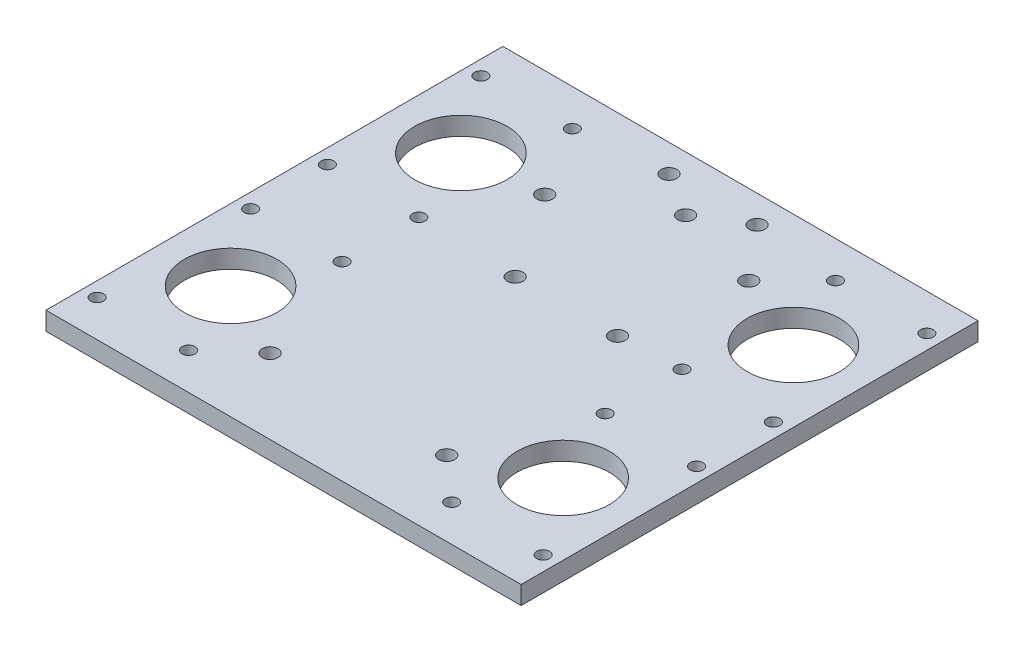
SolidWorks part; units mm, degrees
ref_plane "Front Plane" through (0, 0, 0) normal (0, 0, 1) x (1, 0, 0)
ref_plane "Top Plane" through (0, 0, 0) normal (0, 1, 0) x (1, 0, 0)
ref_plane "Right Plane" through (0, 0, 0) normal (1, 0, 0) x (0, 0, -1)
sketch "Sketch1" plane through (0, 0, 0) normal (0, 1, 0) x (1, 0, 0)
  line L1 (-65, 62.5) -> (65, 62.5)
  line L2 (-65, 62.5) -> (-65, -62.5)
  line L3 (-65, -62.5) -> (65, -62.5)
  line L4 (65, 62.5) -> (65, -62.5)
  line L5 (-65, 62.5) -> (65, -62.5) construction
  line L6 (-65, -62.5) -> (65, 62.5) construction
  point P0 (0, 0)
  dimension "D1" = 130
  dimension "D2" = 125
extrude "Boss-Extrude1" add sketch "Sketch1" along normal blind 5
sketch "Sketch2" plane through (0, 5, 0) normal (0, 1, 0) x (1, 0, 0)
  line L1 (-65, -62.5) -> (65, -62.5) construction
  line L2 (-65, 62.5) -> (-65, -62.5) construction
  circle A0 centre (-61, -52.5) radius 1.75
  circle A1 centre (-36, -52.5) radius 1.75
  circle A2 centre (-36, -10.5) radius 1.75
  circle A3 centre (-61, -10.5) radius 1.75
  circle A4 centre (-45.5, -31.5) radius 12.65
  dimension "D2" = 25.3
  dimension "D7" = 3.5
  dimension "D8" = 3.5
  dimension "D9" = 3.5
  dimension "D10" = 3.5
  dimension "D1" = 19.5
  dimension "D3" = 31
  dimension "D4" = 4
  dimension "D5" = 10
  dimension "D6" = 10
  dimension "D11" = 4
  dimension "D12" = 42
  dimension "D13" = 42
  dimension "D14" = 25
  dimension "D15" = 25
extrude "Cut-Extrude1" cut sketch "Sketch2" against normal blind 10
ref_plane "Plane1" through (0, 0, 0) normal (-1, 0, 0) x (0, 0, 1)
ref_plane "Plane2" through (0, 0, 0) normal (0, 0, 1) x (1, 0, 0)
mirror "Mirror3" about plane through (0, 0, 0) normal (-1, 0, 0) of "Cut-Extrude1"
mirror "Mirror4" about plane through (0, 0, 0) normal (0, 0, 1) of "Mirror3", "Cut-Extrude1"
sketch "Sketch3" plane through (0, 5, 0) normal (0, 1, 0) x (1, 0, 0)
  line L0 (-65, -62.5) -> (65, -62.5) construction
  line L1 (-65, 62.5) -> (-65, -62.5) construction
  line L2 (65, -62.5) -> (65, 62.5) construction
  line L3 (65, 62.5) -> (-65, 62.5) construction
  circle A0 centre (-24.17, -42.03) radius 2.15
  circle A1 centre (24.17, -42.03) radius 2.15
  circle A2 centre (-8.73, 9.6) radius 2.15
  circle A3 centre (19.29, 9.6) radius 2.15
  circle A4 centre (-24.17, 33.11) radius 2.15
  circle A5 centre (24.17, 40.6) radius 2.15
  dimension "D1" = 4.3
  dimension "D6" = 4.3
  dimension "D7" = 4.3
  dimension "D10" = 4.3
  dimension "D11" = 4.3
  dimension "D12" = 4.3
  dimension "D2" = 20.47
  dimension "D3" = 40.83
  dimension "D4" = 20.47
  dimension "D5" = 40.83
  dimension "D8" = 72.1
  dimension "D9" = 56.27
  dimension "D13" = 45.71
  dimension "D14" = 72.1
  dimension "D15" = 29.39
  dimension "D16" = 21.9
  dimension "D17" = 40.83
extrude "Cut-Extrude2" cut sketch "Sketch3" against normal blind 10
sketch "Sketch4" plane through (0, 5, 0) normal (0, 1, 0) x (1, 0, 0)
  line L0 (0, 62.5) -> (0, 47.5) construction
  line L1 (65, 62.5) -> (-65, 62.5) construction
  line L2 (-12.0498, 55) -> (12.0498, 55) construction
  circle A0 centre (0, 47.5) radius 2.15
  circle A1 centre (12.0498, 55) radius 2.15
  circle A2 centre (-12.0498, 55) radius 2.15
  point P9 (0, 55)
  dimension "D2" = 4.3
  dimension "D3" = 4.3
  dimension "D4" = 4.3
  dimension "D1" = 15
  dimension "D5" = 24.0996
extrude "Cut-Extrude3" cut sketch "Sketch4" against normal blind 10
